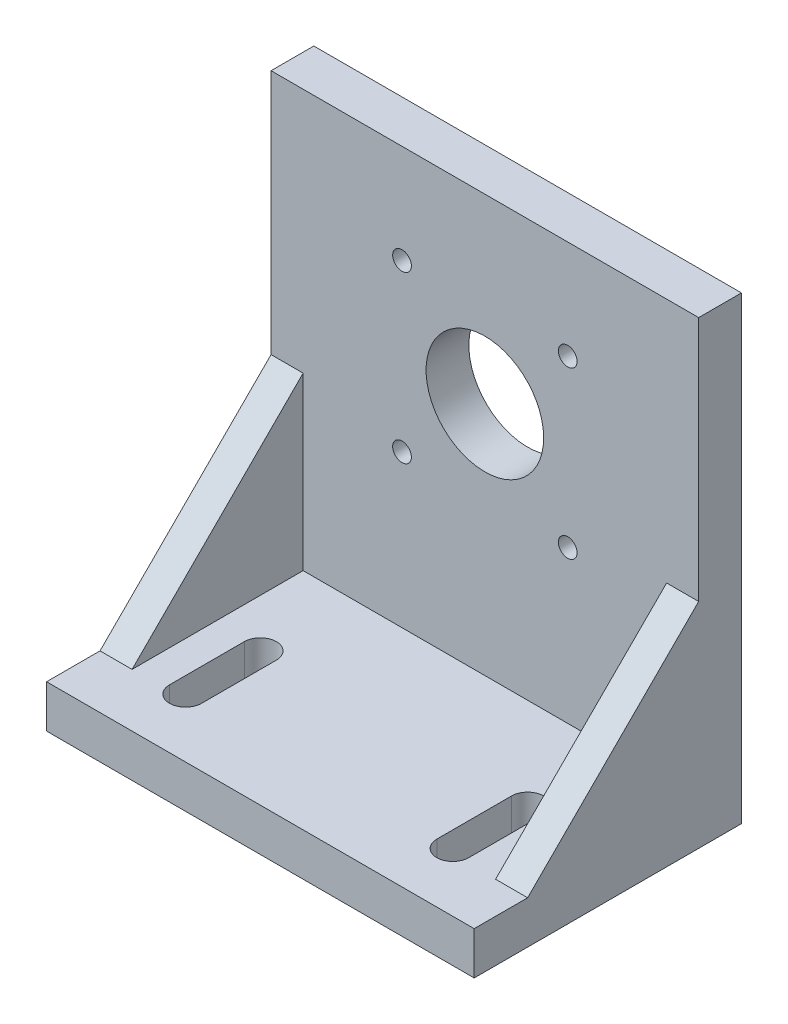
SolidWorks part; units mm, degrees
ref_plane "前视基准面" through (0, 0, 0) normal (0, 0, 1) x (1, 0, 0)
ref_plane "上视基准面" through (0, 0, 0) normal (0, 1, 0) x (1, 0, 0)
ref_plane "右视基准面" through (0, 0, 0) normal (1, 0, 0) x (0, 0, -1)
sketch "草图3" plane through (0, 0, 0) normal (0, 1, 0) x (1, 0, 0)
  line L0 (-40, 8) -> (40, 8)
  line L1 (40, 8) -> (40, -42)
  line L2 (40, -42) -> (-40, -42)
  line L3 (-40, -42) -> (-40, 8)
extrude "凸台-拉伸3" add sketch "草图3" along normal blind 8
sketch "草图4" plane through (0, 0, 0) normal (0, 0, 1) x (1, 0, 0)
  line L0 (-40, 8) -> (40, 8)
  line L1 (40, 8) -> (40, 94)
  line L2 (40, 94) -> (-40, 94)
  line L3 (-40, 94) -> (-40, 8)
extrude "凸台-拉伸4" add sketch "草图4" against normal blind 8
ref_plane "基准面1" through (-40, 0, 0) normal (1, 0, 0) x (0, 0, -1)
ref_plane "基准面2" through (34, 0, 0) normal (1, 0, 0) x (0, 0, -1)
sketch "草图7" plane through (0, 0, 0) normal (0, 0, 1) x (1, 0, 0)
  line L0 (-50, 86) -> (50, 86)
  line L1 (50, 86) -> (50, 104)
  line L2 (50, 104) -> (-50, 104)
  line L3 (-50, 104) -> (-50, 86)
extrude "切除-拉伸1" cut sketch "草图7" against normal mid plane 190
ref_plane "基准面3" through (0, 8, 0) normal (0, 1, 0) x (1, 0, 0)
sketch "草图8" plane through (0, 8, 0) normal (0, 1, 0) x (1, 0, 0)
  line L0 (-22, -17) -> (-22, -31)
  line L1 (-28, -31) -> (-28, -17)
  line L2 (28, -17) -> (28, -31)
  line L3 (22, -31) -> (22, -17)
  arc A0 (-22, -31) -> (-28, -31) centre (-25, -31) cw
  arc A1 (-28, -17) -> (-22, -17) centre (-25, -17) cw
  arc A2 (28, -31) -> (22, -31) centre (25, -31) cw
  arc A3 (22, -17) -> (28, -17) centre (25, -17) cw
extrude "切除-拉伸2" cut sketch "草图8" against normal mid plane 174
sketch "草图9" plane through (0, 0, 0) normal (0, 0, 1) x (1, 0, 0)
  circle A0 centre (0, 52) radius 11
extrude "切除-拉伸3" cut sketch "草图9" against normal through all
sketch "草图10" plane through (0, 0, 0) normal (0, 0, 1) x (1, 0, 0)
  circle A0 centre (-15.5, 67.5) radius 1.75
  circle A1 centre (15.5, 67.5) radius 1.75
  circle A2 centre (-15.5, 36.5) radius 1.75
  circle A3 centre (15.5, 36.5) radius 1.75
extrude "切除-拉伸4" cut sketch "草图10" against normal through all
sketch "草图11" plane through (-40, 0, 0) normal (1, 0, 0) x (0, 0, -1)
  line L0 (0, 8) -> (-32, 8)
  line L1 (-32, 8) -> (0, 40)
  line L2 (0, 40) -> (0, 8)
extrude "凸台-拉伸7" add sketch "草图11" along normal blind 6
sketch "草图12" plane through (34, 0, 0) normal (1, 0, 0) x (0, 0, -1)
  line L0 (0, 8) -> (-32, 8)
  line L1 (-32, 8) -> (0, 40)
  line L2 (0, 40) -> (0, 8)
extrude "凸台-拉伸8" add sketch "草图12" along normal blind 6
